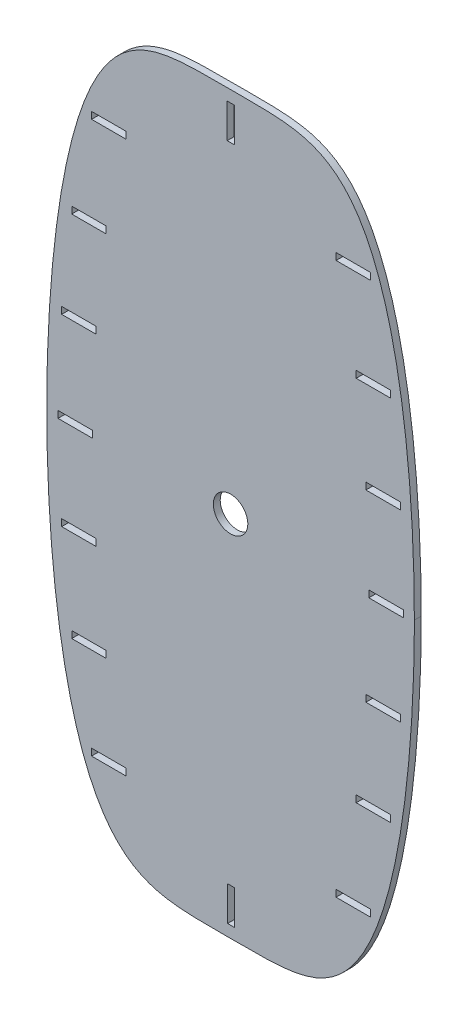
SolidWorks part; units mm, degrees
ref_plane "前视基准面" through (0, 0, 0) normal (0, 0, 1) x (1, 0, 0)
ref_plane "上视基准面" through (0, 0, 0) normal (0, 1, 0) x (1, 0, 0)
ref_plane "右视基准面" through (0, 0, 0) normal (1, 0, 0) x (0, 0, -1)
other "Configuration Table"
sketch "草图1" plane through (0, 0, 0) normal (0, 0, 1) x (1, 0, 0)
  line L1 (-80, 0) -> (80, 0) construction
  line L15 (0, 200.5149) -> (0, -282.6549) construction
  spline S0 degree 4 poles (-80, 0) (-80, 6.6995) (-79.8133, 20.0663) (-78.9758, 40.103) (-76.9006, 63.4094) (-74.1294, 83.2574) (-71.2981, 97.6967) (-69.0993, 106.812) (-66.7086, 115.204) (-64.4894, 121.9026) (-61.7767, 128.7729) (-58.6103, 135.2089) (-55.7484, 140.0386) (-52.418, 144.6922) (-48.6444, 148.9327) (-43.9019, 152.8957) (-38.6389, 155.7974) (-33.774, 157.5515) (-29.4379, 158.5861) (-25.7339, 159.1853) (-22.0518, 159.5691) (-18.4063, 159.7976) (-14.0532, 159.9452) (-8.9946, 160) (-3.2327, 160) (3.2327, 160) (8.9946, 160) (14.0532, 159.9452) (18.4063, 159.7976) (22.0518, 159.5691) (25.7339, 159.1853) (29.4379, 158.5861) (33.774, 157.5515) (38.6389, 155.7974) (43.9019, 152.8957) (48.6444, 148.9327) (52.418, 144.6922) (55.7484, 140.0386) (58.6103, 135.2089) (61.7768, 128.7729) (64.4891, 121.9024) (66.709, 115.2043) (70.0138, 103.5975) (73.4335, 87.8956) (76.6047, 66.7392) (78.9754, 40.1027) (79.8135, 20.0664) (80, 6.6995) (80, 0) knots 0 0 0 0 0 0.064993 0.129673 0.194485 0.226896 0.259308 0.272364 0.28542 0.311533 0.327739 0.343945 0.354938 0.36593 0.383191 0.398872 0.414552 0.423882 0.433212 0.442069 0.450926 0.459783 0.468639 0.48432 0.5 0.51568 0.531361 0.540217 0.549074 0.557931 0.566788 0.576118 0.585448 0.601128 0.616809 0.63407 0.645062 0.656055 0.672261 0.688467 0.71458 0.727636 0.740692 0.805515 0.870327 0.935007 1 1 1 1 1 construction
  spline S1 degree 4 poles (-80, 0) (-80, 6.6995) (-79.8133, 20.0663) (-78.9758, 40.103) (-76.9006, 63.4094) (-74.1294, 83.2574) (-71.2981, 97.6967) (-69.0993, 106.812) (-66.7086, 115.204) (-64.4894, 121.9026) (-61.7767, 128.7729) (-58.6103, 135.2089) (-55.7484, 140.0386) (-52.418, 144.6922) (-48.6444, 148.9327) (-43.9019, 152.8957) (-38.6389, 155.7974) (-33.774, 157.5515) (-29.4379, 158.5861) (-25.7339, 159.1853) (-22.0518, 159.5691) (-18.4063, 159.7976) (-14.0532, 159.9452) (-8.9946, 160) (-3.2327, 160) (3.2327, 160) (8.9946, 160) (14.0532, 159.9452) (18.4063, 159.7976) (22.0518, 159.5691) (25.7339, 159.1853) (29.4379, 158.5861) (33.774, 157.5515) (38.6389, 155.7974) (43.9019, 152.8957) (48.6444, 148.9327) (52.418, 144.6922) (55.7484, 140.0386) (58.6103, 135.2089) (61.7768, 128.7729) (64.4891, 121.9024) (66.709, 115.2043) (70.0138, 103.5975) (73.4335, 87.8956) (76.6047, 66.7392) (78.9754, 40.1027) (79.8135, 20.0664) (80, 6.6995) (80, 0) knots 0 0 0 0 0 0.064993 0.129673 0.194485 0.226896 0.259308 0.272364 0.28542 0.311533 0.327739 0.343945 0.354938 0.36593 0.383191 0.398872 0.414552 0.423882 0.433212 0.442069 0.450926 0.459783 0.468639 0.48432 0.5 0.51568 0.531361 0.540217 0.549074 0.557931 0.566788 0.576118 0.585448 0.601128 0.616809 0.63407 0.645062 0.656055 0.672261 0.688467 0.71458 0.727636 0.740692 0.805515 0.870327 0.935007 1 1 1 1 1
  spline S2 degree 4 poles (-80, 0) (-80, -6.6995) (-79.8133, -20.0663) (-78.9758, -40.103) (-76.9006, -63.4094) (-74.1294, -83.2574) (-71.2981, -97.6967) (-69.0993, -106.812) (-66.7086, -115.204) (-64.4894, -121.9026) (-61.7767, -128.7729) (-58.6103, -135.2089) (-55.7484, -140.0386) (-52.418, -144.6922) (-48.6444, -148.9327) (-43.9019, -152.8957) (-38.6389, -155.7974) (-33.774, -157.5515) (-29.4379, -158.5861) (-25.7339, -159.1853) (-22.0518, -159.5691) (-18.4063, -159.7976) (-14.0532, -159.9452) (-8.9946, -160) (-3.2327, -160) (3.2327, -160) (8.9946, -160) (14.0532, -159.9452) (18.4063, -159.7976) (22.0518, -159.5691) (25.7339, -159.1853) (29.4379, -158.5861) (33.774, -157.5515) (38.6389, -155.7974) (43.9019, -152.8957) (48.6444, -148.9327) (52.418, -144.6922) (55.7484, -140.0386) (58.6103, -135.2089) (61.7768, -128.7729) (64.4891, -121.9024) (66.709, -115.2043) (70.0138, -103.5975) (73.4335, -87.8956) (76.6047, -66.7392) (78.9754, -40.1027) (79.8135, -20.0664) (80, -6.6995) (80, 0) knots 0 0 0 0 0 0.064993 0.129673 0.194485 0.226896 0.259308 0.272364 0.28542 0.311533 0.327739 0.343945 0.354938 0.36593 0.383191 0.398872 0.414552 0.423882 0.433212 0.442069 0.450926 0.459783 0.468639 0.48432 0.5 0.51568 0.531361 0.540217 0.549074 0.557931 0.566788 0.576118 0.585448 0.601128 0.616809 0.63407 0.645062 0.656055 0.672261 0.688467 0.71458 0.727636 0.740692 0.805515 0.870327 0.935007 1 1 1 1 1
  point P6 (71.6044, -44.6187)
  point P7 (76.067, -59.2294)
  point P9 (-71.2684, 97.3457)
extrude "凸台-拉伸1" add sketch "草图1" along normal blind 3
sketch "草图3" plane through (0, 0, 3) normal (0, 0, 1) x (1, 0, 0)
  line L1 (-1.2996, -155) -> (1.7004, -155)
  line L2 (-1.2996, -155) -> (-1.2996, -140)
  line L3 (-1.2996, -140) -> (1.7004, -140)
  line L4 (1.7004, -155) -> (1.7004, -140)
  line L5 (45.9056, -121.5) -> (60.9056, -121.5)
  line L6 (45.9056, -121.5) -> (45.9056, -118.5)
  line L7 (45.9056, -118.5) -> (60.9056, -118.5)
  line L8 (60.9056, -121.5) -> (60.9056, -118.5)
  line L9 (-45.5048, -118.5) -> (-60.5048, -118.5)
  line L10 (-45.5048, -118.5) -> (-45.5048, -121.5)
  line L11 (-45.5048, -121.5) -> (-60.5048, -121.5)
  line L12 (-60.5048, -118.5) -> (-60.5048, -121.5)
  line L13 (-73.4996, -41.5) -> (-58.4996, -41.5)
  line L14 (-73.4996, -41.5) -> (-73.4996, -38.5)
  line L15 (-73.4996, -38.5) -> (-58.4996, -38.5)
  line L16 (-58.4996, -41.5) -> (-58.4996, -38.5)
  line L17 (58.9004, -41.5) -> (73.9004, -41.5)
  line L18 (58.9004, -41.5) -> (58.9004, -38.5)
  line L19 (58.9004, -38.5) -> (73.9004, -38.5)
  line L20 (73.9004, -41.5) -> (73.9004, -38.5)
  line L21 (60.2004, -1.5) -> (75.2004, -1.5)
  line L22 (60.2004, -1.5) -> (60.2004, 1.5)
  line L23 (60.2004, 1.5) -> (75.2004, 1.5)
  line L24 (75.2004, -1.5) -> (75.2004, 1.5)
  line L25 (58.9004, 38.5) -> (73.9004, 38.5)
  line L26 (58.9004, 38.5) -> (58.9004, 41.5)
  line L27 (58.9004, 41.5) -> (73.9004, 41.5)
  line L28 (73.9004, 38.5) -> (73.9004, 41.5)
  line L29 (-75.0934, -1.5) -> (-60.0621, -1.5)
  line L30 (-75.0934, -1.5) -> (-75.0934, 1.5)
  line L31 (-75.0934, 1.5) -> (-60.0621, 1.5)
  line L32 (-60.0621, -1.5) -> (-60.0621, 1.5)
  line L33 (-73.4996, 38.5) -> (-58.4996, 38.5)
  line L34 (-73.4996, 38.5) -> (-73.4996, 41.5)
  line L35 (-73.4996, 41.5) -> (-58.4996, 41.5)
  line L36 (-58.4996, 38.5) -> (-58.4996, 41.5)
  line L37 (-60.4801, 118.5266) -> (-45.4801, 118.5266)
  line L38 (-60.4801, 118.5266) -> (-60.4801, 121.5139)
  line L39 (-60.4801, 121.5139) -> (-45.4801, 121.5139)
  line L40 (-45.4801, 118.5266) -> (-45.4801, 121.5139)
  line L41 (45.9303, 118.5266) -> (60.9303, 118.5266)
  line L42 (45.9303, 118.5266) -> (45.9303, 121.5139)
  line L43 (45.9303, 121.5139) -> (60.9303, 121.5139)
  line L44 (60.9303, 118.5266) -> (60.9303, 121.5139)
  line L45 (-1.439, 154.9293) -> (1.7004, 154.9293)
  line L46 (-1.439, 154.9293) -> (-1.439, 139.9957)
  line L47 (-1.439, 139.9957) -> (1.7004, 139.9957)
  line L48 (1.7004, 154.9293) -> (1.7004, 139.9957)
extrude "切除-拉伸1" cut sketch "草图3" against normal blind 3
sketch "草图5" plane through (0, 0, 3) normal (0, 0, 1) x (1, 0, 0)
  line L1 (-69.1178, -81.5) -> (-54.1178, -81.5)
  line L2 (-69.1178, -81.5) -> (-69.1178, -78.5)
  line L3 (-69.1178, -78.5) -> (-54.1178, -78.5)
  line L4 (-54.1178, -81.5) -> (-54.1178, -78.5)
  line L5 (54.6822, -81.5) -> (69.6822, -81.5)
  line L6 (54.6822, -81.5) -> (54.6822, -78.5)
  line L7 (54.6822, -78.5) -> (69.6822, -78.5)
  line L8 (69.6822, -81.5) -> (69.6822, -78.5)
  line L9 (54.6822, 78.5) -> (69.6822, 78.5)
  line L10 (54.6822, 78.5) -> (54.6822, 81.5)
  line L11 (54.6822, 81.5) -> (69.6822, 81.5)
  line L12 (69.6822, 78.5) -> (69.6822, 81.5)
  line L13 (-69.1178, 78.5) -> (-54.1178, 78.5)
  line L14 (-69.1178, 78.5) -> (-69.1178, 81.5)
  line L15 (-69.1178, 81.5) -> (-54.1178, 81.5)
  line L16 (-54.1178, 78.5) -> (-54.1178, 81.5)
extrude "切除-拉伸2" cut sketch "草图5" against normal blind 3
sketch "草图7" plane through (0, 0, 0) normal (0, 0, -1) x (-1, 0, 0)
  circle A0 centre (0, 0) radius 7.5
  dimension "D1" = 15
extrude "切除-拉伸3" cut sketch "草图7" against normal blind 3
